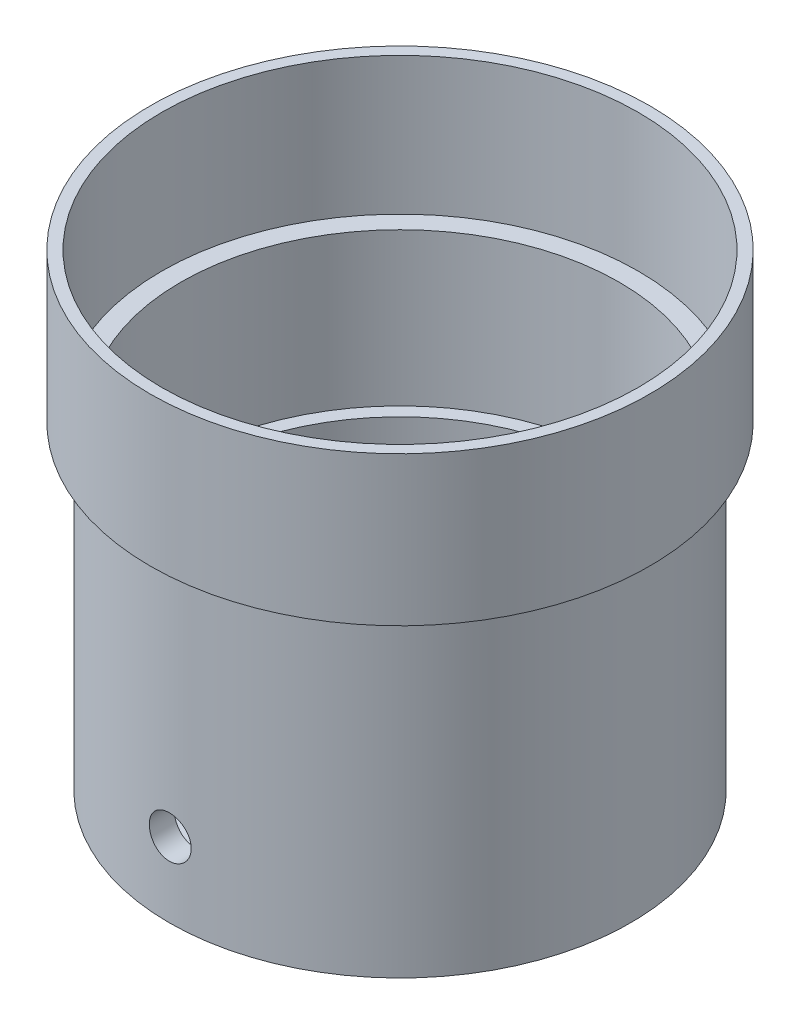
SolidWorks part; units mm, degrees
ref_plane "Front Plane" through (0, 0, 0) normal (0, 0, 1) x (1, 0, 0)
ref_plane "Top Plane" through (0, 0, 0) normal (0, 1, 0) x (1, 0, 0)
ref_plane "Right Plane" through (0, 0, 0) normal (1, 0, 0) x (0, 0, -1)
sketch "Sketch1" plane through (0, 0, 0) normal (0, 0, 1) x (1, 0, 0)
  line L0 (0, 0) -> (0, 61.5387) construction
  line L1 (53.975, 0) -> (53.975, 42.5)
  line L6 (53.975, 0) -> (60.475, 0)
  line L7 (60.475, 0) -> (60.475, 79.5)
  line L8 (53.975, 42.5) -> (57.475, 42.5)
  line L9 (57.475, 42.5) -> (57.475, 82.5)
  line L10 (57.475, 82.5) -> (62.475, 82.5)
  line L11 (65.475, 92.7908) -> (65.475, -5.7786) construction
  line L13 (65.475, 79.5) -> (60.475, 79.5)
  line L14 (65.475, 118.56) -> (51.575, 118.56) construction
  line L15 (0, 70.3) -> (82.1787, 70.3) construction
  line L17 (62.475, 82.5) -> (62.475, 118.56)
  line L18 (62.475, 118.56) -> (65.475, 118.56)
  line L19 (65.475, 118.56) -> (65.475, 79.5)
  point P11 (60.475, 39.75)
  point P14 (55.725, 42.5)
  dimension "D1" = 53.975
  dimension "D2" = 6.5
  dimension "D3" = 42.5
  dimension "D4" = 3
  dimension "D5" = 40
  dimension "D6" = 5
  dimension "D7" = 27.8
  dimension "D8" = 48.26
  dimension "D9" = 3
  dimension "D10" = 3
revolve "Revolve1" add sketch "Sketch1" angle 360 about L0
sketch "Sketch3" plane through (0, 0, 0) normal (0, -1, 0) x (1, 0, 0)
  circle A0 centre (0, 0) radius 60.475 construction
  circle A1 centre (0, 0) radius 60.475
extrude "Boss-Extrude1" add sketch "Sketch3" along normal blind 4 contours A1
ref_plane "Plane2" through (0, 0, 0) normal (0, 1, 0) x (1, 0, 0)
sketch "Sketch5" plane through (0, 0, 0) normal (0, 0, 1) x (1, 0, 0)
  line L0 (0, -0.6469) -> (0, 47.8832) construction
  line L2 (59.3725, 0) -> (-59.3725, 0) construction
  circle A0 centre (0, 15.5) radius 5.5
  dimension "D1" = 11
  dimension "D2" = 15.5
extrude "Cut-Extrude1" cut sketch "Sketch5" against normal blind 4 and the other way through all
